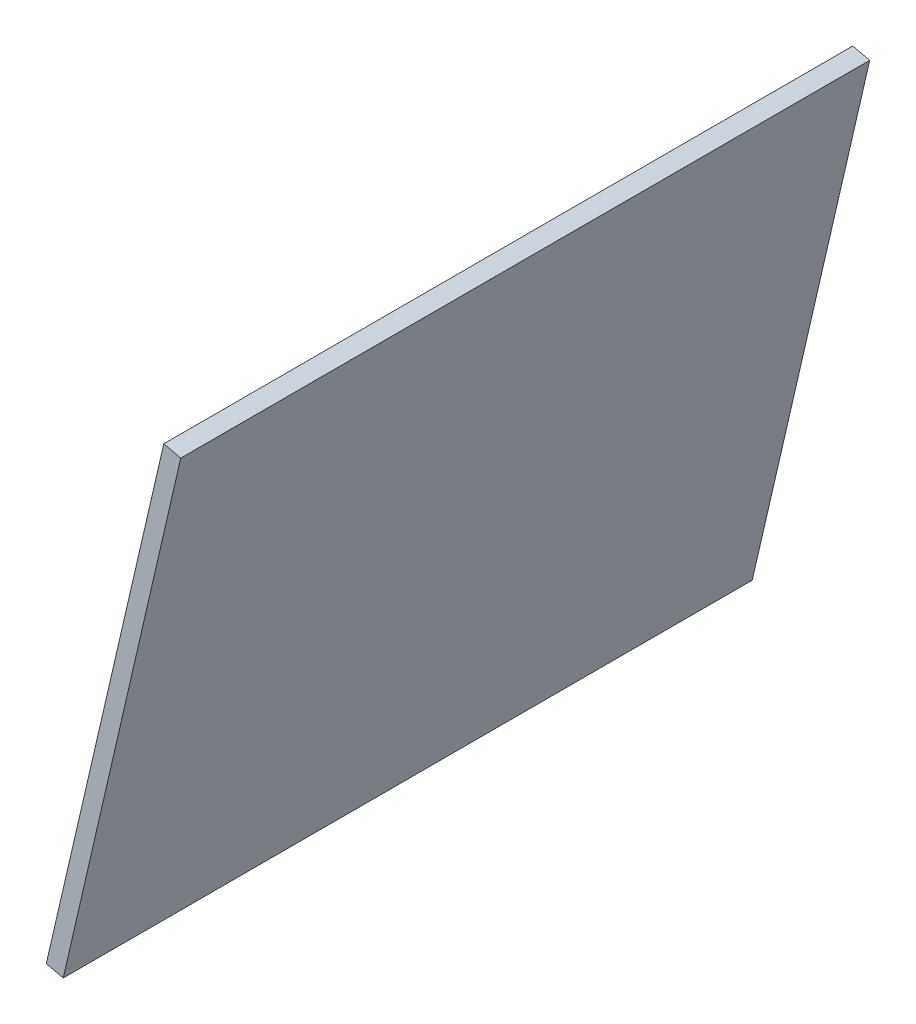
SolidWorks part; units mm, degrees
ref_plane "Front Plane" through (0, 0, 0) normal (0, 0, 1) x (1, 0, 0)
ref_plane "Top Plane" through (0, 0, 0) normal (0, 1, 0) x (1, 0, 0)
ref_plane "Right Plane" through (0, 0, 0) normal (1, 0, 0) x (0, 0, -1)
sketch "Sketch1" plane through (0, 0, 0) normal (0, 0, 1) x (1, 0, 0)
  line L0 (130.4243, 1639.6605) -> (117.4836, 1583.6084) construction
  line L1 (174.2078, 1829.308) -> (105.6428, 1532.32)
  line L2 (105.6428, 1532.32) -> (95.7432, 1534.6055)
  line L4 (95.7432, 1534.6055) -> (164.3082, 1831.5935)
  line L5 (164.3082, 1831.5935) -> (174.2078, 1829.308)
  line L6 (10.16, 2052.32) -> (91.4769, 2052.32) construction
  dimension "D1" = 520
  dimension "D2" = 304.8
extrude "Boss-Extrude1" add sketch "Sketch1" along normal blind 402
